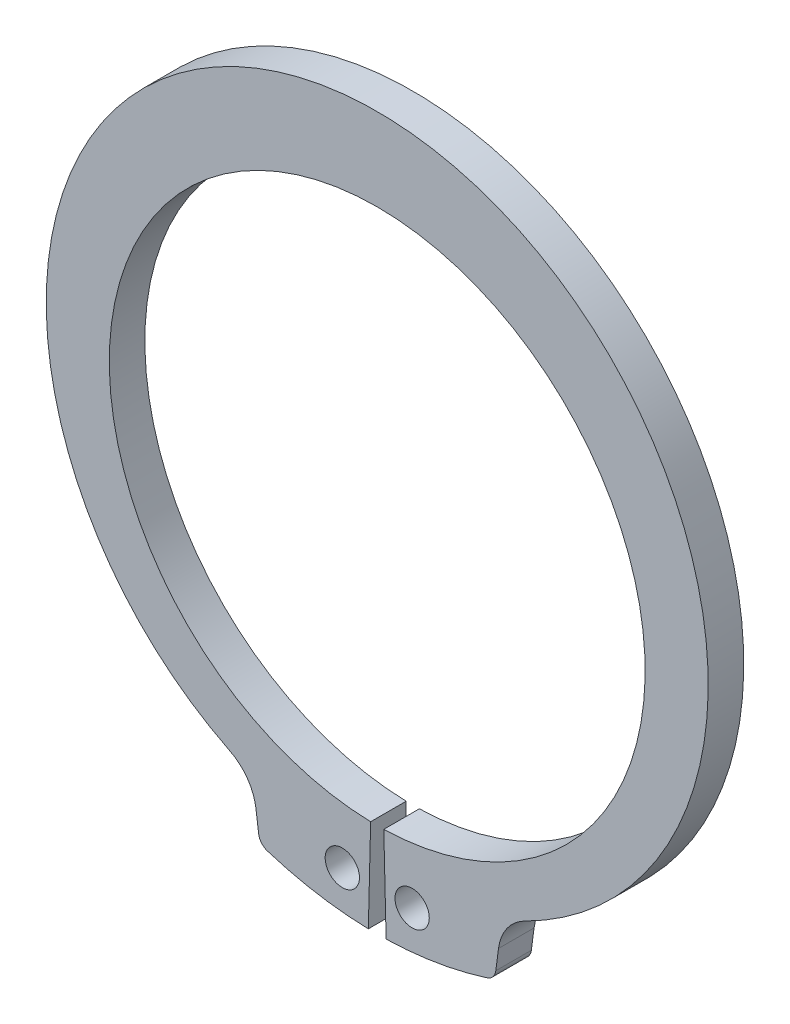
SolidWorks part; units mm, degrees
ref_plane "Plane1" through (0, 0, 0) normal (0, 0, 1) x (1, 0, 0)
ref_plane "Plane2" through (0, 0, 0) normal (0, 1, 0) x (1, 0, 0)
ref_plane "Plane3" through (0, 0, 0) normal (1, 0, 0) x (0, 0, -1)
sketch "Clipboard" plane through (0, 0, 0) normal (0, 0, 1) x (1, 0, 0)
  line L0 (0, 0) -> (6.5, 0)
  line L1 (0, 0) -> (0, 3.6)
  line L2 (0, 0) -> (0, -7.4)
  circle A0 centre (0, 0) radius 1.35
  circle A1 centre (0, 0) radius 22.5
  dimension "HoleDia" = 2.7
  dimension "ShaftDia" = 45
  dimension "LargeSection" = 6.5
  dimension "SmallSection" = 3.6
  dimension "LugSection" = 7.4
sketch "BodySke" plane through (0, 0, 0) normal (0, 0, 1) x (1, 0, 0)
  line L0 (-1.5431, 0) -> (1.5431, 0) construction
  line L1 (0, 0) -> (0, 27.6) construction
  line L2 (0.5182, -21.0936) -> (0.7, -28.4914)
  line L3 (-0.5182, -21.0936) -> (-0.7, -28.4914)
  line L4 (0, 0) -> (13.3182, -25.1967) construction
  line L5 (0, 0) -> (-13.3182, -25.1967) construction
  line L7 (9.5519, -24.7009) -> (9.337, -26.3336)
  line L8 (-9.5519, -24.7009) -> (-9.337, -26.3336)
  circle A0 centre (0, 0) radius 21.1 construction
  arc A1 (0.5182, -21.0936) -> (-0.5182, -21.0936) centre (0, 0) ccw
  arc A2 (11.5424, -21.8372) -> (-11.5424, -21.8372) centre (0, 1.534) ccw construction
  arc A3 (0.7, -28.4914) -> (8.649, -27.1559) centre (0, 0) ccw
  arc A4 (11.6241, -21.7966) -> (9.5519, -24.7009) centre (13.3182, -25.1967) ccw
  arc A5 (-9.5519, -24.7009) -> (-11.6241, -21.7966) centre (-13.3182, -25.1967) ccw
  arc A6 (-8.649, -27.1559) -> (-0.7, -28.4914) centre (0, 0) ccw
  arc A7 (11.6241, -21.7966) -> (-11.6241, -21.7966) centre (0, 1.534) ccw
  arc A8 (-9.6991, -23.5834) -> (9.6991, -23.5834) centre (0, 0) ccw construction
  circle A9 centre (2.75, -25.3513) radius 1.35
  circle A10 centre (-2.75, -25.3513) radius 1.35
  arc A11 (9.337, -26.3336) -> (8.649, -27.1559) centre (8.3455, -26.2031) cw
  arc A12 (-9.337, -26.3336) -> (-8.649, -27.1559) centre (-8.3455, -26.2031) ccw
  point P28 (9.2551, -26.9554)
  point P31 (-9.2551, -26.9554)
  dimension "GrooveDia" = 42.2
  dimension "LugRad" = 28.5
  dimension "HoleOffsetRad" = 25.5
  dimension "HoleDia" = 2.7
  dimension "D3" = 1
  dimension "LargeRad" = 27.6
  dimension "SmallRad" = 24.7
  dimension "SmallAngle" = 55.719
  dimension "D2" = 15
  dimension "HoleSpacing" = 5.5
  dimension "Gap" = 1.4
extrude "Body" add sketch "BodySke" against normal blind 2.8
sketch "NotSke" plane through (0, 0, 0) normal (0, 0, 1) x (1, 0, 0)
  line L0 (2.75, -24.0013) -> (2.75, -26.7013)
  line L1 (2.75, -26.7013) -> (-2.75, -26.7013)
  line L2 (-2.75, -26.7013) -> (-2.75, -24.0013)
  line L3 (-2.75, -24.0013) -> (2.75, -24.0013)
  circle A0 centre (2.75, -25.3513) radius 1.35 construction
  circle A1 centre (-2.75, -25.3513) radius 1.35 construction
extrude "Notch" [suppressed] cut sketch "NotSke" against normal through all
equation "' \"ShaftDia@Clipboard\" = 10"
equation "' \"Thickness@Body\" = 0.9"
equation "' \"GrooveDia@BodySke\" = 9.4"
equation "' \"LugSection@Clipboard\" = 2.6"
equation "' \"LargeSection@Clipboard\" = 1.7"
equation "' \"SmallSection@Clipboard\" = 1.0"
equation "' \"HoleDia@Clipboard\" = 1.0"
equation "' \"ShaftDia@Clipboard\" = 30"
equation "' \"Thickness@Body\" = 2.4"
equation "' \"GrooveDia@BodySke\" = 28.2"
equation "' \"LugSection@Clipboard\" = 5.6"
equation "' \"LargeSection@Clipboard\" = 4.5"
equation "' \"SmallSection@Clipboard\" = 2.5"
equation "' \"HoleDia@Clipboard\" = 2.3"
equation "\"Gap@BodySke\" =  \"Thickness@Body\" / 2"
equation "\"LargeRad@BodySke\" =  \"GrooveDia@BodySke\" / 2 +  \"LargeSection@Clipboard\""
equation "\"SmallRad@BodySke\" =  \"GrooveDia@BodySke\" / 2 +  \"SmallSection@Clipboard\""
equation "\"LugRad@BodySke\" = \"GrooveDia@BodySke\" / 2 + \"LugSection@Clipboard\""
equation "\"HoleOffsetRad@BodySke\" = (  \"ShaftDia@Clipboard\" / 2 + \"LugRad@BodySke\" ) / 2"
equation "\"HoleSpacing@BodySke\" = \"Gap@BodySke\"  * 2 +  \"HoleDia@Clipboard\""
equation "\"HoleDia@BodySke\" =  \"HoleDia@Clipboard\""
equation "\"SmallAngle@BodySke\" = atn(\"HoleSpacing@BodySke\" / 2 / sqr(\"HoleOffsetRad@BodySke\"  * \"HoleOffsetRad@BodySke\" - (\"HoleSpacing@BodySke\" / 2) * (\"HoleSpacing@BodySke\" / 2) ))  * 9 * ( 180 / 3.141593)"
